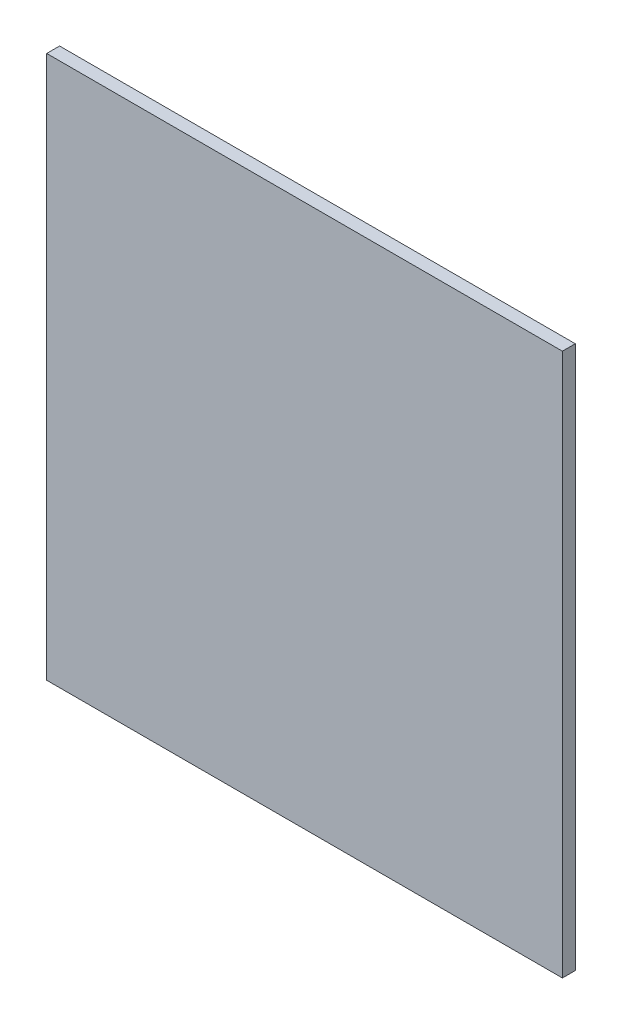
SolidWorks part; units mm, degrees
material "Kiefer"
ref_plane "Ebene vorne" through (0, 0, 0) normal (0, 0, 1) x (1, 0, 0)
ref_plane "Ebene oben" through (0, 0, 0) normal (0, 1, 0) x (1, 0, 0)
ref_plane "Ebene rechts" through (0, 0, 0) normal (1, 0, 0) x (0, 0, -1)
sketch "Skizze1" plane through (0, 0, 0) normal (0, 0, 1) x (1, 0, 0)
  line L0 (0, 0) -> (0, 40.512) construction
  line L2 (380, 400) -> (-380, 400)
  line L3 (380, 400) -> (380, -400)
  line L4 (380, -400) -> (-380, -400)
  line L5 (-380, 400) -> (-380, -400)
  line L6 (380, 400) -> (-380, -400) construction
  line L7 (380, -400) -> (-380, 400) construction
  dimension "D1" = 760
  dimension "D2" = 800
extrude "Aufsatz-Linear austragen1" add sketch "Skizze1" along normal mid plane 19
